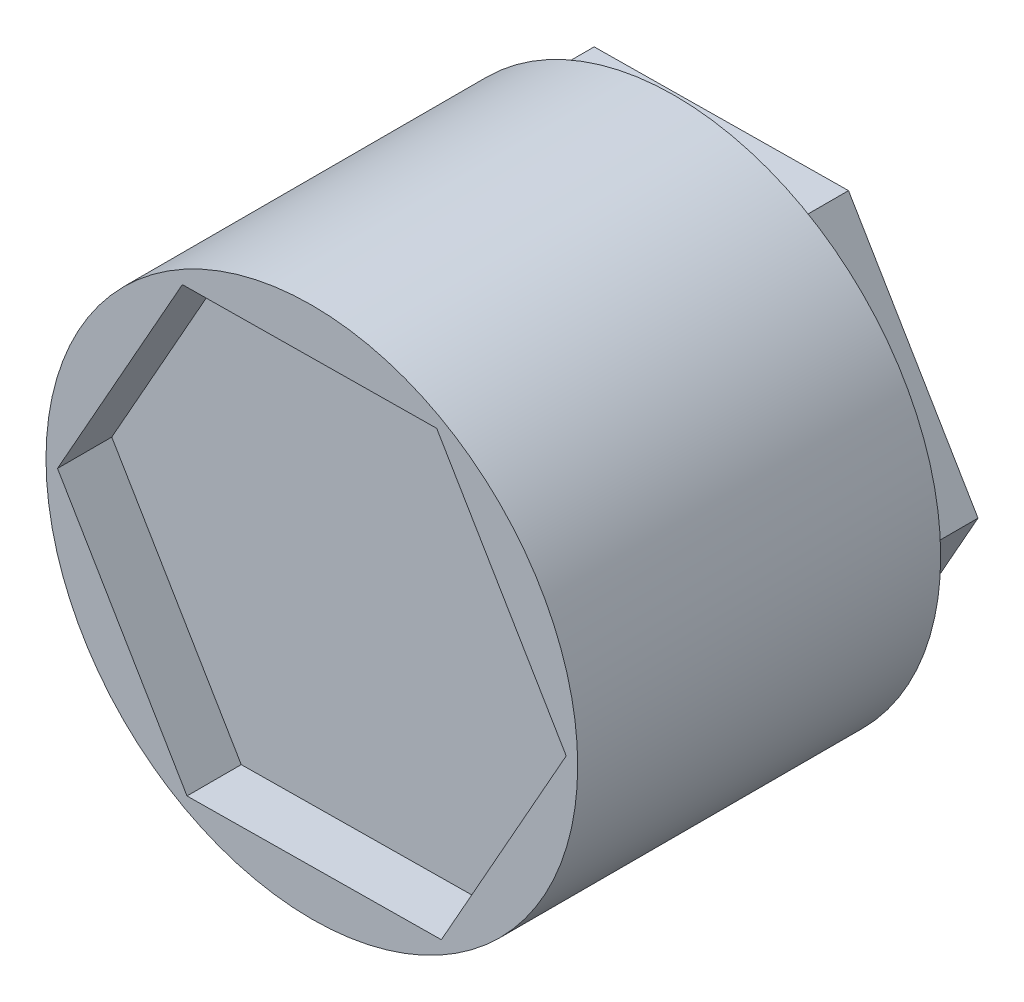
SolidWorks part; units mm, degrees
ref_plane "Front Plane" through (0, 0, 0) normal (1, 0, 0) x (0, 1, 0)
ref_plane "Top Plane" through (0, 0, 0) normal (0, 0, 1) x (0, 1, 0)
ref_plane "Right Plane" through (0, 0, 0) normal (0, 1, 0) x (-1, 0, 0)
sketch "Sketch1" plane through (0, 0, 0) normal (0, 0, 1) x (0, 1, 0)
  line L1 (20.1756, 11.9331) -> (-0.2466, 23.4391)
  line L2 (-0.2466, 23.4391) -> (-20.4222, 11.506)
  line L3 (-20.4222, 11.506) -> (-20.1756, -11.9331)
  line L4 (-20.1756, -11.9331) -> (0.2466, -23.4391)
  line L5 (0.2466, -23.4391) -> (20.4222, -11.506)
  line L6 (20.4222, -11.506) -> (20.1756, 11.9331)
  circle A0 centre (0, 0) radius 20.3 construction
extrude "Boss-Extrude1" add sketch "Sketch1" along normal blind 4.5
sketch "Sketch3" plane through (0, 0, 4.5) normal (0, 0, 1) x (1, 0, 0)
  circle A0 centre (0, 0) radius 24.5
  dimension "D1" = 49
extrude "Boss-Extrude2" add sketch "Sketch3" along normal blind 33.45
sketch "Sketch4" plane through (0, 0, 37.95) normal (0, 0, 1) x (1, 0, 0)
  line L1 (11.506, 20.4222) -> (-11.9331, 20.1756)
  line L2 (-11.9331, 20.1756) -> (-23.4391, -0.2466)
  line L3 (-23.4391, -0.2466) -> (-11.506, -20.4222)
  line L4 (-11.506, -20.4222) -> (11.9331, -20.1756)
  line L5 (11.9331, -20.1756) -> (23.4391, 0.2466)
  line L6 (23.4391, 0.2466) -> (11.506, 20.4222)
  circle A0 centre (0, 0) radius 20.3 construction
extrude "Cut-Extrude1" cut sketch "Sketch4" against normal blind 5
